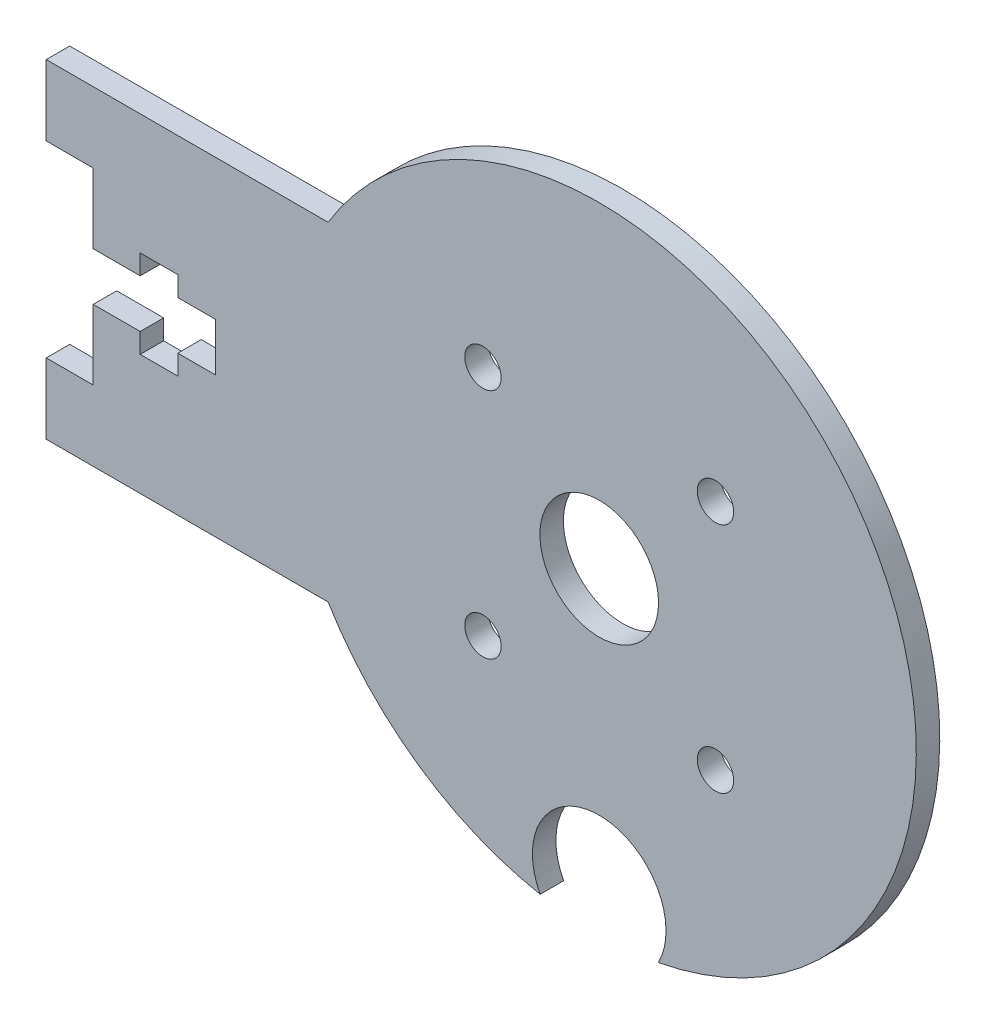
SolidWorks part; units mm, degrees
ref_plane "前视基准面" through (0, 0, 0) normal (0, 0, 1) x (1, 0, 0)
ref_plane "上视基准面" through (0, 0, 0) normal (0, 1, 0) x (1, 0, 0)
ref_plane "右视基准面" through (0, 0, 0) normal (1, 0, 0) x (0, 0, -1)
sketch "草图1" plane through (0, 0, 0) normal (0, 0, 1) x (1, 0, 0)
  line L0 (0, 0) -> (0, -27) construction
  line L1 (0, 0) -> (-16.3098, -16.3098) construction
  line L2 (0, 14) -> (-59.4313, 14) construction
  line L3 (0, -14) -> (0, 14) construction
  line L4 (0, -14) -> (-56.8959, -14) construction
  line L5 (-23.0868, -14) -> (-43.0868, -14)
  line L6 (-23.0868, 14) -> (-43.0868, 14)
  line L7 (-43.0868, 14) -> (-47.0868, 14)
  line L8 (-47.0868, 14) -> (-47.0868, 8)
  line L9 (-47.0868, 8) -> (-43.0868, 8)
  line L10 (-43.0868, -14) -> (-47.0868, -14)
  line L11 (-47.0868, -14) -> (-47.0868, -8)
  line L12 (-47.0868, -8) -> (-43.0868, -8)
  line L13 (-43.0868, 2.05) -> (-43.0868, -2.05) construction
  line L14 (-43.0868, 0) -> (0, 0) construction
  line L15 (-43.0868, -2.05) -> (-39.0868, -2.05)
  line L16 (-39.0868, -2.05) -> (-39.0868, -3.7414)
  line L17 (-39.0868, -3.7414) -> (-35.8868, -3.7414)
  line L18 (-35.8868, -3.7414) -> (-35.8868, -2.05)
  line L19 (-35.8868, -2.05) -> (-32.6868, -2.05)
  line L20 (-32.6868, -2.05) -> (-32.6868, 2.05)
  line L21 (-39.0868, 2.05) -> (-39.0868, 3.7414)
  line L22 (-35.8868, 3.7414) -> (-35.8868, 2.05)
  line L23 (-35.8868, 2.05) -> (-32.6868, 2.05)
  line L24 (-39.0868, 3.7414) -> (-35.8868, 3.7414)
  line L25 (-43.0868, 2.05) -> (-39.0868, 2.05)
  line L26 (-43.0868, -2.05) -> (-43.0868, -8)
  line L27 (-43.0868, 2.05) -> (-43.0868, 8)
  circle A0 centre (0, 0) radius 5.05
  circle A1 centre (0, 0) radius 27 construction
  circle A2 centre (0, 0) radius 14 construction
  circle A3 centre (-9.8995, -9.8995) radius 1.55
  circle A4 centre (-9.8995, 9.8995) radius 1.55
  circle A5 centre (9.8995, 9.8995) radius 1.55
  circle A6 centre (9.8995, -9.8995) radius 1.55
  arc A9 (-5.0274, -26.5278) -> (5.0274, -26.5278) centre (0, 0) cw construction
  circle A10 centre (0, 0) radius 12 construction
  arc A11 (-5.0274, -26.5278) -> (5.0274, -26.5278) centre (0, -23.8649) cw
  arc A12 (-23.0868, 14) -> (5.0274, -26.5278) centre (0, 0) cw
  arc A13 (-23.0868, -14) -> (-5.0274, -26.5278) centre (0, 0) ccw
  point P48 (-32.6868, 0)
  dimension "D1" = 10.1
  dimension "D2" = 54
  dimension "D4" = 28
  dimension "D5" = 4
  dimension "D6" = 24
  dimension "D3" = 45
  dimension "D7" = 20
  dimension "D8" = 20
  dimension "D9" = 4
  dimension "D10" = 6
  dimension "D11" = 4
  dimension "D12" = 6
  dimension "D13" = 2.05
  dimension "D14" = 3.2
  dimension "D15" = 4
extrude "凸台-拉伸1" add sketch "草图1" along normal blind 2
